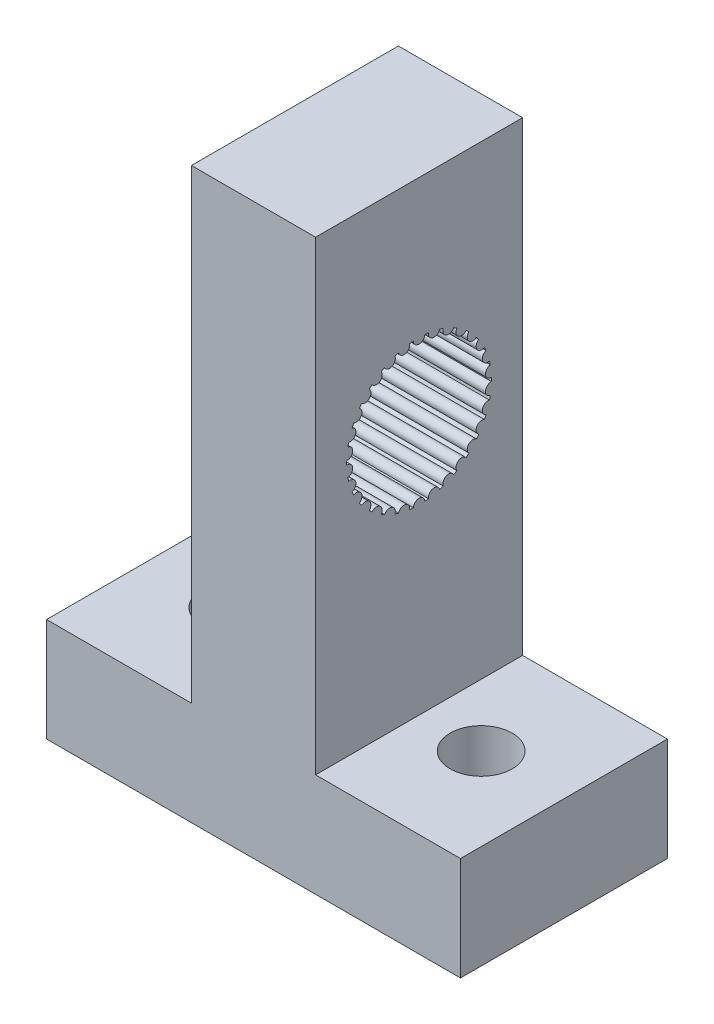
SolidWorks part; units mm, degrees
ref_plane "Alzado" through (0, 0, 0) normal (0, 0, 1) x (1, 0, 0)
ref_plane "Planta" through (0, 0, 0) normal (0, 1, 0) x (1, 0, 0)
ref_plane "Vista lateral" through (0, 0, 0) normal (1, 0, 0) x (0, 0, -1)
sketch "Croquis1" plane through (0, 0, 0) normal (0, 0, 1) x (1, 0, 0)
  line L0 (3, 13.75) -> (-3, 13.75)
  line L1 (-3, 13.75) -> (-3, -8.75)
  line L2 (-3, -8.75) -> (-10, -8.75)
  line L3 (-10, -8.75) -> (-10, -13.75)
  line L4 (-10, -13.75) -> (10, -13.75)
  line L5 (0, -13.75) -> (0, 13.75)
  line L6 (0, 28.2693) -> (0, -29.9167) construction
  line L7 (10, -8.75) -> (10, -13.75)
  line L8 (3, -8.75) -> (10, -8.75)
  line L9 (3, 13.75) -> (3, -8.75)
  point P10 (0, 0)
  dimension "D1" = 27.5
  dimension "D2" = 3
  dimension "D3" = 10
  dimension "D4" = 5
extrude "Saliente-Extruir1" add sketch "Croquis1" along normal mid plane 10 contours L9 L0 L5 L4 L7 L8 | L4 L5 L0 L1 L2 L3
sketch "Croquis4" plane through (3, 0, 0) normal (1, 0, 0) x (0, 0, -1)
  line L0 (0, 12.8173) -> (0, -5.1206) construction
  line L1 (-5, -13.75) -> (5, -13.75) construction
  circle A0 centre (0, 3.55) radius 3.5
  dimension "D2" = 7
  dimension "D1" = 17.3
extrude "Cortar-Extruir3" cut sketch "Croquis4" against normal blind 15
sketch "Croquis5" plane through (0, -13.75, 0) normal (0, -1, 0) x (1, 0, 0)
  line L0 (12.601, 0) -> (-13.2445, 0) construction
  line L1 (0, 4.0216) -> (0, -6.2022) construction
  circle A0 centre (-6, 0) radius 1.5
  circle A1 centre (6, 0) radius 1.5
  dimension "D1" = 3
  dimension "D2" = 6
extrude "Cortar-Extruir4" cut sketch "Croquis5" against normal blind 10
sketch "Croquis6" plane through (0, 0, 0) normal (1, 0, 0) x (0, 0, -1)
  line L0 (0, 7.05) -> (0, 0) construction
  circle A0 centre (0, 3.55) radius 3.5 construction
  arc A1 (0.2748, 7.0392) -> (-0.2748, 7.0392) centre (0, 3.55) ccw
  circle A2 centre (0, 3.55) radius 3.225 construction
  arc A3 (-0.2748, 7.0392) -> (0.2748, 7.0392) centre (0, 7.05) ccw
  arc A4 (0.9942, 6.9058) -> (0.4567, 7.0201) centre (0, 3.55) ccw
  arc A5 (0.4567, 7.0201) -> (0.9942, 6.9058) centre (0.7277, 6.9735) ccw
  arc A6 (1.6702, 6.6258) -> (1.1682, 6.8493) centre (0, 3.55) ccw
  arc A7 (1.1682, 6.8493) -> (1.6702, 6.6258) centre (1.4236, 6.7474) ccw
  arc A8 (2.2732, 6.2113) -> (1.8286, 6.5343) centre (0, 3.55) ccw
  arc A9 (1.8286, 6.5343) -> (2.2732, 6.2113) centre (2.0572, 6.3816) ccw
  arc A10 (2.7768, 5.6805) -> (2.4091, 6.0889) centre (0, 3.55) ccw
  arc A11 (2.4091, 6.0889) -> (2.7768, 5.6805) centre (2.601, 5.892) ccw
  arc A12 (3.1591, 5.0566) -> (2.8843, 5.5326) centre (0, 3.55) ccw
  arc A13 (2.8843, 5.5326) -> (3.1591, 5.0566) centre (3.0311, 5.3) ccw
  arc A14 (3.4033, 4.3669) -> (3.2335, 4.8896) centre (0, 3.55) ccw
  arc A15 (3.2335, 4.8896) -> (3.4033, 4.3669) centre (3.3287, 4.6316) ccw
  arc A16 (3.4988, 3.6414) -> (3.4414, 4.188) centre (0, 3.55) ccw
  arc A17 (3.4414, 4.188) -> (3.4988, 3.6414) centre (3.4808, 3.9158) ccw
  arc A18 (3.4414, 2.912) -> (3.4988, 3.4586) centre (0, 3.55) ccw
  arc A19 (3.4988, 3.4586) -> (3.4414, 2.912) centre (3.4808, 3.1842) ccw
  arc A20 (3.2335, 2.2104) -> (3.4033, 2.7331) centre (0, 3.55) ccw
  arc A21 (3.4033, 2.7331) -> (3.2335, 2.2104) centre (3.3287, 2.4684) ccw
  arc A22 (2.8843, 1.5674) -> (3.1591, 2.0434) centre (0, 3.55) ccw
  arc A23 (3.1591, 2.0434) -> (2.8843, 1.5674) centre (3.0311, 1.8) ccw
  arc A24 (2.4091, 1.0111) -> (2.7768, 1.4195) centre (0, 3.55) ccw
  arc A25 (2.7768, 1.4195) -> (2.4091, 1.0111) centre (2.601, 1.208) ccw
  arc A26 (1.8286, 0.5657) -> (2.2732, 0.8887) centre (0, 3.55) ccw
  arc A27 (2.2732, 0.8887) -> (1.8286, 0.5657) centre (2.0572, 0.7184) ccw
  arc A28 (1.1682, 0.2507) -> (1.6702, 0.4742) centre (0, 3.55) ccw
  arc A29 (1.6702, 0.4742) -> (1.1682, 0.2507) centre (1.4236, 0.3526) ccw
  arc A30 (0.4567, 0.0799) -> (0.9942, 0.1942) centre (0, 3.55) ccw
  arc A31 (0.9942, 0.1942) -> (0.4567, 0.0799) centre (0.7277, 0.1265) ccw
  arc A32 (-0.2748, 0.0608) -> (0.2748, 0.0608) centre (0, 3.55) ccw
  arc A33 (0.2748, 0.0608) -> (-0.2748, 0.0608) centre (0, 0.05) ccw
  arc A34 (-0.9942, 0.1942) -> (-0.4567, 0.0799) centre (0, 3.55) ccw
  arc A35 (-0.4567, 0.0799) -> (-0.9942, 0.1942) centre (-0.7277, 0.1265) ccw
  arc A36 (-1.6702, 0.4742) -> (-1.1682, 0.2507) centre (0, 3.55) ccw
  arc A37 (-1.1682, 0.2507) -> (-1.6702, 0.4742) centre (-1.4236, 0.3526) ccw
  arc A38 (-2.2732, 0.8887) -> (-1.8286, 0.5657) centre (0, 3.55) ccw
  arc A39 (-1.8286, 0.5657) -> (-2.2732, 0.8887) centre (-2.0572, 0.7184) ccw
  arc A40 (-2.7768, 1.4195) -> (-2.4091, 1.0111) centre (0, 3.55) ccw
  arc A41 (-2.4091, 1.0111) -> (-2.7768, 1.4195) centre (-2.601, 1.208) ccw
  arc A42 (-3.1591, 2.0434) -> (-2.8843, 1.5674) centre (0, 3.55) ccw
  arc A43 (-2.8843, 1.5674) -> (-3.1591, 2.0434) centre (-3.0311, 1.8) ccw
  arc A44 (-3.4033, 2.7331) -> (-3.2335, 2.2104) centre (0, 3.55) ccw
  arc A45 (-3.2335, 2.2104) -> (-3.4033, 2.7331) centre (-3.3287, 2.4684) ccw
  arc A46 (-3.4988, 3.4586) -> (-3.4414, 2.912) centre (0, 3.55) ccw
  arc A47 (-3.4414, 2.912) -> (-3.4988, 3.4586) centre (-3.4808, 3.1842) ccw
  arc A48 (-3.4414, 4.188) -> (-3.4988, 3.6414) centre (0, 3.55) ccw
  arc A49 (-3.4988, 3.6414) -> (-3.4414, 4.188) centre (-3.4808, 3.9158) ccw
  arc A50 (-3.2335, 4.8896) -> (-3.4033, 4.3669) centre (0, 3.55) ccw
  arc A51 (-3.4033, 4.3669) -> (-3.2335, 4.8896) centre (-3.3287, 4.6316) ccw
  arc A52 (-2.8843, 5.5326) -> (-3.1591, 5.0566) centre (0, 3.55) ccw
  arc A53 (-3.1591, 5.0566) -> (-2.8843, 5.5326) centre (-3.0311, 5.3) ccw
  arc A54 (-2.4091, 6.0889) -> (-2.7768, 5.6805) centre (0, 3.55) ccw
  arc A55 (-2.7768, 5.6805) -> (-2.4091, 6.0889) centre (-2.601, 5.892) ccw
  arc A56 (-1.8286, 6.5343) -> (-2.2732, 6.2113) centre (0, 3.55) ccw
  arc A57 (-2.2732, 6.2113) -> (-1.8286, 6.5343) centre (-2.0572, 6.3816) ccw
  arc A58 (-1.1682, 6.8493) -> (-1.6702, 6.6258) centre (0, 3.55) ccw
  arc A59 (-1.6702, 6.6258) -> (-1.1682, 6.8493) centre (-1.4236, 6.7474) ccw
  arc A60 (-0.4567, 7.0201) -> (-0.9942, 6.9058) centre (0, 3.55) ccw
  arc A61 (-0.9942, 6.9058) -> (-0.4567, 7.0201) centre (-0.7277, 6.9735) ccw
  point P10 (0, 6.775)
  dimension "D1" = 6.45
  dimension "D2" = 30
extrude "Saliente-Extruir2" add sketch "Croquis6" along normal blind 3 and the other way blind 3
